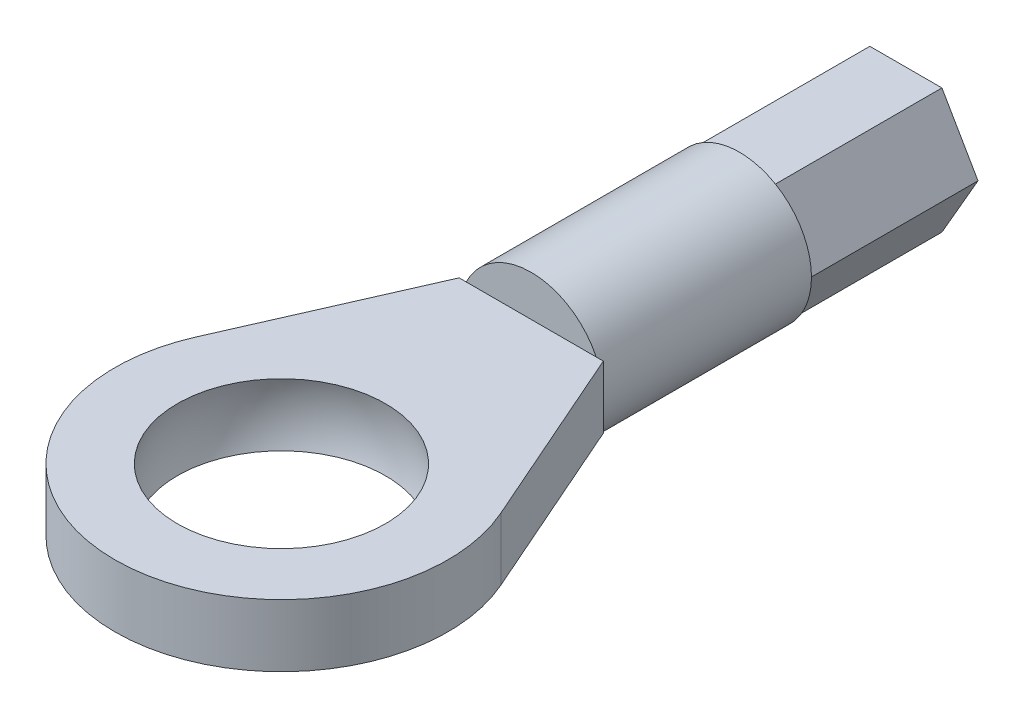
SolidWorks part; units mm, degrees
material "尼龙 101"
ref_plane "前视基准面" through (0, 0, 0) normal (0, 0, 1) x (1, 0, 0)
ref_plane "上视基准面" through (0, 0, 0) normal (0, 1, 0) x (1, 0, 0)
ref_plane "右视基准面" through (0, 0, 0) normal (1, 0, 0) x (0, 0, -1)
sketch "草图1" plane through (0, 0, 0) normal (0, 0, 1) x (1, 0, 0)
  line L2 (0.866, 1.5) -> (-0.866, 1.5)
  line L3 (-0.866, 1.5) -> (-1.7321, 0)
  line L4 (-1.7321, 0) -> (-0.866, -1.5)
  line L5 (-0.866, -1.5) -> (0.866, -1.5)
  line L6 (0.866, -1.5) -> (1.7321, 0)
  line L7 (1.7321, 0) -> (0.866, 1.5)
  circle A0 centre (0, 0) radius 1
  circle A1 centre (0, 0) radius 1.5 construction
  dimension "D1" = 2
  dimension "D2" = 3
extrude "凸台-拉伸1" add sketch "草图1" along normal blind 4
sketch "草图2" plane through (0, 0, 0) normal (0, 0, 1) x (1, 0, 0)
  circle A0 centre (0, 0) radius 1.7321
extrude "凸台-拉伸2" add sketch "草图2" along normal blind 5 from surface at 4 starting at face at (0, 0, 4)
sketch "草图3" plane through (0, 0, 0) normal (0, 1, 0) x (1, 0, 0)
  line L0 (0, 0) -> (0, -15) construction
  line L1 (-1.7321, -9) -> (-3.6619, -13.3904)
  line L2 (1.7321, -9) -> (3.6619, -13.3904)
  line L3 (-1.7321, -9) -> (1.7321, -9)
  arc A0 (-3.6619, -13.3904) -> (3.6619, -13.3904) centre (0, -15) ccw
  circle A1 centre (0, -15) radius 2.5
  dimension "D1" = 8
  dimension "D3" = 5
  dimension "D2" = 15
extrude "凸台-拉伸3" add sketch "草图3" along normal blind 0.75 and the other way blind 0.75
sketch "草图4" plane through (0, 0, 0) normal (1, 0, 0) x (0, 0, -1)
  line L0 (0, 0) -> (-15, 0) construction
  line L1 (-15, 0) -> (-17.5, 0) construction
  line L2 (-17.5, 0) -> (-17.5, 0.75) construction
  line L3 (-17.5, 0.75) -> (-15, 0) construction
  line L4 (-15, -2.6101) -> (-15, 2.6101)
  arc A1 (-15, 2.6101) -> (-15, -2.6101) centre (-15, 0) ccw
  point P9 (-15, 0)
  dimension "D3" = 0.75
  dimension "D1" = 15
  dimension "D2" = 2.5
revolve "切除-旋转2" cut sketch "草图4" angle 360 about L4
